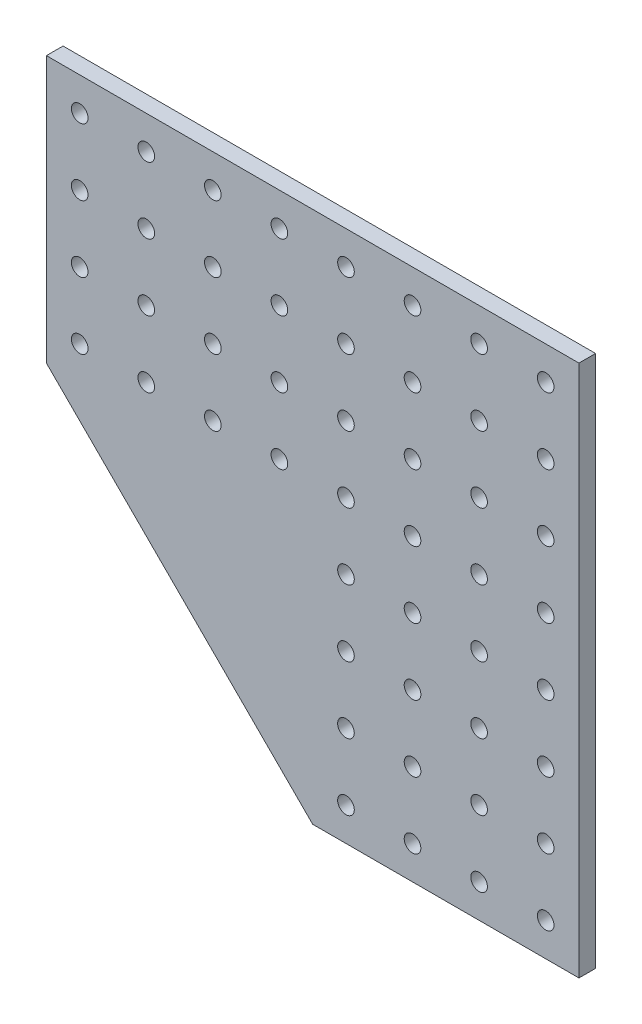
SolidWorks part; units mm, degrees
ref_plane "Front Plane" through (0, 0, 0) normal (0, 0, 1) x (1, 0, 0)
ref_plane "Top Plane" through (0, 0, 0) normal (0, 1, 0) x (1, 0, 0)
ref_plane "Right Plane" through (0, 0, 0) normal (1, 0, 0) x (0, 0, -1)
ref_plane "Plane1"
sketch "Sketch1" plane through (0, 0, 0) normal (0, 0, 1) x (1, 0, 0)
  line L0 (-72.7046, 193.4128) -> (-72.7046, 91.8128)
  line L1 (-72.7046, 91.8128) -> (28.8954, -9.7872)
  line L2 (28.8954, -9.7872) -> (130.4954, -9.7872)
  line L3 (130.4954, -9.7872) -> (130.4954, 193.4128)
  line L4 (130.4954, 193.4128) -> (-72.7046, 193.4128)
  dimension "D1" = 101.6
  dimension "D2" = 101.6
  dimension "D3" = 203.2
  dimension "D4" = 203.2
extrude "Extrusion1" add sketch "Sketch1" along normal blind 6.35
hole_wizard "Hole1" positions "Sketch3" profile "Sketch2" legacy end condition through all
sketch "Sketch3" plane through (0, 0, 6.35) normal (0, 0, 1) x (1, 0, 0)
  point P1 (-60.0046, 180.7128)
  point P2 (-34.6046, 180.7128)
  point P3 (-60.0046, 155.3128)
  point P4 (-34.6046, 155.3128)
  point P5 (-60.0046, 129.9128)
  point P6 (-34.6046, 129.9128)
  point P7 (-60.0046, 104.5128)
  point P8 (-34.6046, 104.5128)
  point P9 (117.7954, 79.1128)
  point P10 (117.7954, 53.7128)
  point P11 (92.3954, 79.1128)
  point P12 (92.3954, 53.7128)
  point P13 (-9.2046, 180.7128)
  point P14 (-9.2046, 155.3128)
  point P15 (-9.2046, 129.9128)
  point P16 (-9.2046, 104.5128)
  point P17 (16.1954, 180.7128)
  point P18 (16.1954, 155.3128)
  point P19 (16.1954, 129.9128)
  point P20 (16.1954, 104.5128)
  point P21 (41.5954, 180.7128)
  point P22 (41.5954, 155.3128)
  point P23 (41.5954, 129.9128)
  point P24 (41.5954, 104.5128)
  point P25 (66.9954, 180.7128)
  point P26 (66.9954, 155.3128)
  point P27 (66.9954, 129.9128)
  point P28 (66.9954, 104.5128)
  point P29 (92.3954, 180.7128)
  point P30 (92.3954, 155.3128)
  point P31 (92.3954, 129.9128)
  point P32 (92.3954, 104.5128)
  point P33 (117.7954, 180.7128)
  point P34 (117.7954, 155.3128)
  point P35 (117.7954, 129.9128)
  point P36 (117.7954, 104.5128)
  point P37 (117.7954, 28.3128)
  point P38 (92.3954, 28.3128)
  point P39 (117.7954, 2.9128)
  point P40 (92.3954, 2.9128)
  point P41 (66.9954, 79.1128)
  point P42 (66.9954, 53.7128)
  point P43 (66.9954, 28.3128)
  point P44 (66.9954, 2.9128)
  point P45 (41.5954, 79.1128)
  point P46 (41.5954, 53.7128)
  point P47 (41.5954, 28.3128)
  point P48 (41.5954, 2.9128)
sketch "Sketch2" plane through (-60.0046, 180.7128, 6.35) normal (1, 0, 0) x (0, -1, 0)
  line L0 (0, 0) -> (0, 6.35)
  line L1 (0, 6.35) -> (3.175, 6.35)
  line L2 (3.175, 6.35) -> (3.175, 0)
  line L3 (3.175, 0) -> (0, 0)
  line L4 (0, 110) -> (0, -10) construction
  dimension "Diameter" = 6.35
  dimension "Depth" = 6.35
